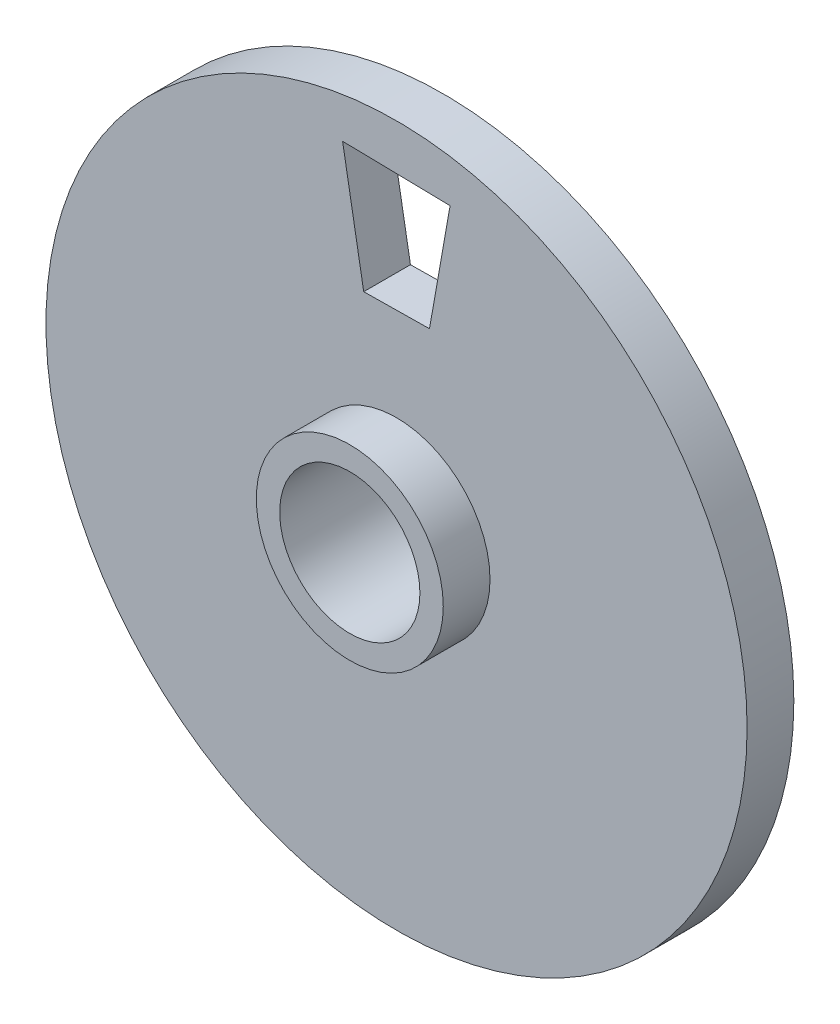
SolidWorks part; units mm, degrees
ref_plane "Спереди" through (0, 0, 0) normal (0, 0, 1) x (1, 0, 0)
ref_plane "Сверху" through (0, 0, 0) normal (0, 1, 0) x (1, 0, 0)
ref_plane "Справа" through (0, 0, 0) normal (1, 0, 0) x (0, 0, -1)
sketch "Эскиз1" plane through (0, 0, 0) normal (0, 0, 1) x (1, 0, 0)
  circle A0 centre (0, 0) radius 3
  circle A1 centre (0, 0) radius 4
  dimension "D1" = 6
  dimension "D2" = 8
extrude "Бобышка-Вытянуть1" add sketch "Эскиз1" along normal blind 2
sketch "Эскиз2" plane through (0, 0, 2) normal (0, 0, 1) x (1, 0, 0)
  line L0 (0, -1000) -> (0, 49000) construction
  line L1 (173.6482, -984.8078) -> (-8508.7607, 48255.5799) construction
  line L2 (-173.6482, -984.8078) -> (8508.7607, 48255.5799) construction
  line L3 (-1000, 13) -> (49000, 13) construction
  line L4 (-1000, 0) -> (49000, 0) construction
  line L5 (-1000, 8) -> (49000, 8) construction
  line L6 (-1.4042, 7.9635) -> (-2.3074, 13.0862)
  line L7 (-2.3074, 13.0862) -> (2.2923, 13)
  line L8 (2.2923, 13) -> (1.4106, 8)
  line L9 (1.4106, 8) -> (-1.4042, 7.9635)
  circle A0 centre (0, 0) radius 3
  circle A1 centre (0, 0) radius 15
  dimension "D1" = 30
  dimension "D2" = 13
  dimension "D3" = 8
extrude "Бобышка-Вытянуть2" add sketch "Эскиз2" along normal blind 2
sketch "Эскиз3" plane through (0, 0, 4) normal (0, 0, 1) x (1, 0, 0)
  circle A0 centre (0, 0) radius 3
  circle A1 centre (0, 0) radius 4
  dimension "D1" = 6
  dimension "D2" = 8
extrude "Бобышка-Вытянуть3" add sketch "Эскиз3" along normal blind 2
